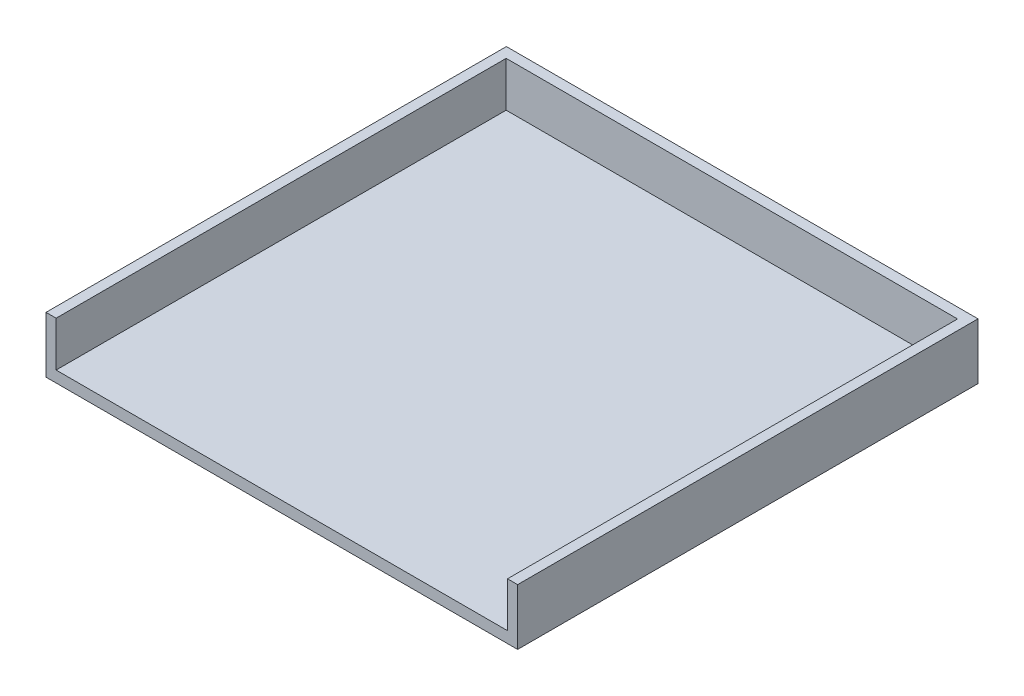
SolidWorks part; units mm, degrees
ref_plane "Спереди" through (0, 0, 0) normal (0, 0, 1) x (1, 0, 0)
ref_plane "Сверху" through (0, 0, 0) normal (0, 1, 0) x (1, 0, 0)
ref_plane "Справа" through (0, 0, 0) normal (1, 0, 0) x (0, 0, -1)
sketch "Эскиз1" plane through (0, 0, 0) normal (0, 1, 0) x (1, 0, 0)
  line L1 (5.0138, -12.126) -> (110.0138, -12.126)
  line L2 (5.0138, -12.126) -> (5.0138, -114.626)
  line L3 (5.0138, -114.626) -> (110.0138, -114.626)
  line L4 (110.0138, -12.126) -> (110.0138, -114.626)
  dimension "D1" = 105
  dimension "D2" = 102.5
extrude "Бобышка-Вытянуть1" add sketch "Эскиз1" along normal blind 2.5
sketch "Эскиз2" plane through (0, 2.5, 0) normal (0, 1, 0) x (1, 0, 0)
  line L1 (5.0138, -12.126) -> (110.0138, -12.126)
  line L2 (5.0138, -12.126) -> (5.0138, -114.626)
  line L3 (5.0138, -114.626) -> (7.2638, -114.626)
  line L4 (110.0138, -12.126) -> (110.0138, -114.626)
  line L5 (7.2638, -14.426) -> (107.7638, -14.426)
  line L6 (7.2638, -14.426) -> (7.2638, -112.9094)
  line L8 (107.7638, -14.426) -> (107.7638, -112.9094)
  line L11 (7.2638, -112.9094) -> (7.2638, -114.626)
  line L13 (107.7638, -112.9094) -> (107.7638, -114.626)
  line L14 (107.7638, -114.626) -> (110.0138, -114.626)
  dimension "D1" = 100.5
  dimension "D2" = 98.4834
extrude "Бобышка-Вытянуть2" add sketch "Эскиз2" along normal blind 10
